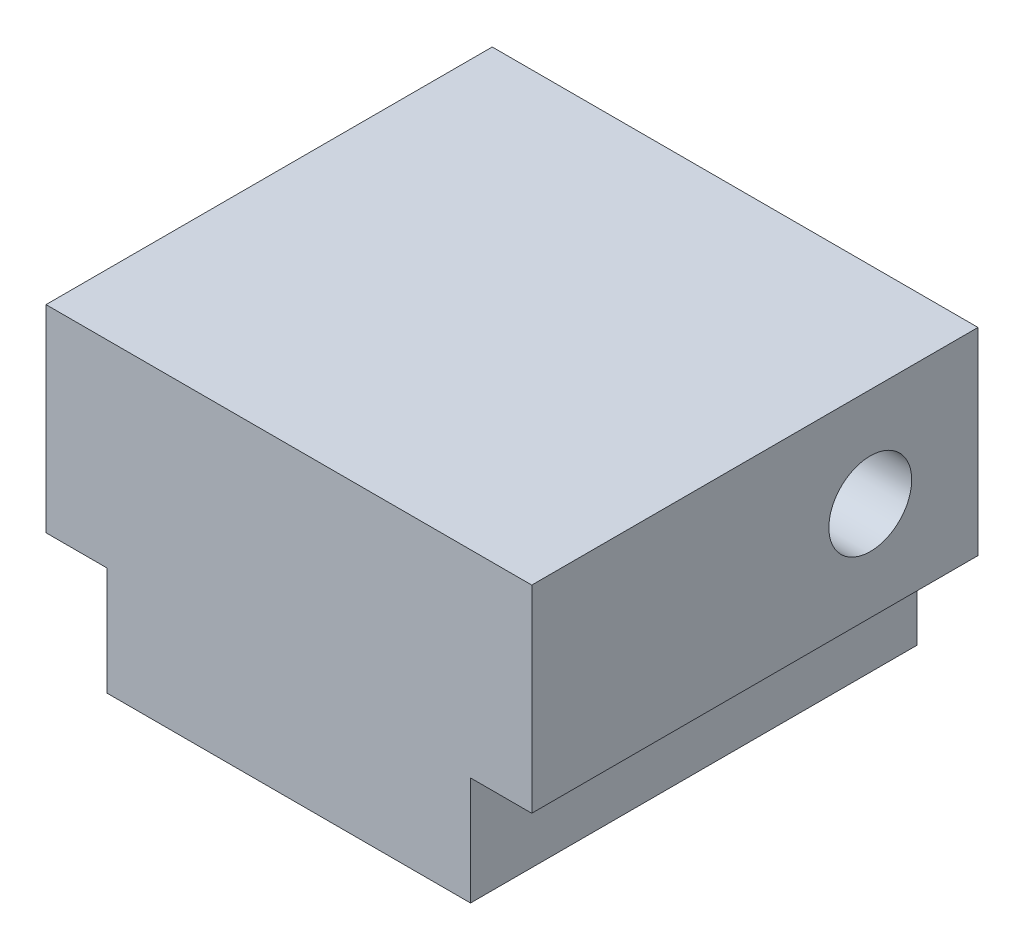
SolidWorks part; units mm, degrees
material "Brass"
ref_plane "Front Plane" through (0, 0, 0) normal (0, 0, 1) x (1, 0, 0)
ref_plane "Top Plane" through (0, 0, 0) normal (0, 1, 0) x (1, 0, 0)
ref_plane "Right Plane" through (0, 0, 0) normal (1, 0, 0) x (0, 0, -1)
sketch "Sketch1" plane through (0, 0, 0) normal (0, 1, 0) x (1, 0, 0)
  line L0 (-38.1, 35) -> (38.1, -35) construction
  line L1 (-38.1, 35) -> (38.1, 35)
  line L2 (-38.1, 35) -> (-38.1, -35)
  line L3 (-38.1, -35) -> (38.1, -35)
  line L4 (38.1, 35) -> (38.1, -35)
  line L5 (-38.1, -35) -> (38.1, 35) construction
  dimension "D1" = 76.2
  dimension "D2" = 70
extrude "Boss-Extrude1" add sketch "Sketch1" along normal blind 31
sketch "Sketch2" plane through (38.1, 0, 0) normal (1, 0, 0) x (0, 0, -1)
  line L0 (35, 31) -> (35, 0) construction
  circle A0 centre (18.1, 15.5) radius 6.5
  dimension "D2" = 13
  dimension "D1" = 16.9
extrude "Cut-Extrude1" cut sketch "Sketch2" against normal through all
sketch "Sketch4" plane through (0, 0, 0) normal (0, -1, 0) x (1, 0, 0)
  line L0 (-38.1, 35) -> (38.1, 35) construction
  line L1 (-28.4945, 35) -> (28.4945, 35)
  line L2 (-28.4945, 35) -> (-28.4945, -35)
  line L3 (-28.4945, -35) -> (28.4945, -35)
  line L4 (28.4945, 35) -> (28.4945, -35)
  line L5 (38.1, -35) -> (-38.1, -35) construction
  line L6 (-28.4945, 35) -> (28.4945, -35) construction
  line L7 (28.4945, 35) -> (-28.4945, -35) construction
  dimension "D1" = 56.989
extrude "Boss-Extrude2" add sketch "Sketch4" along normal blind 17
